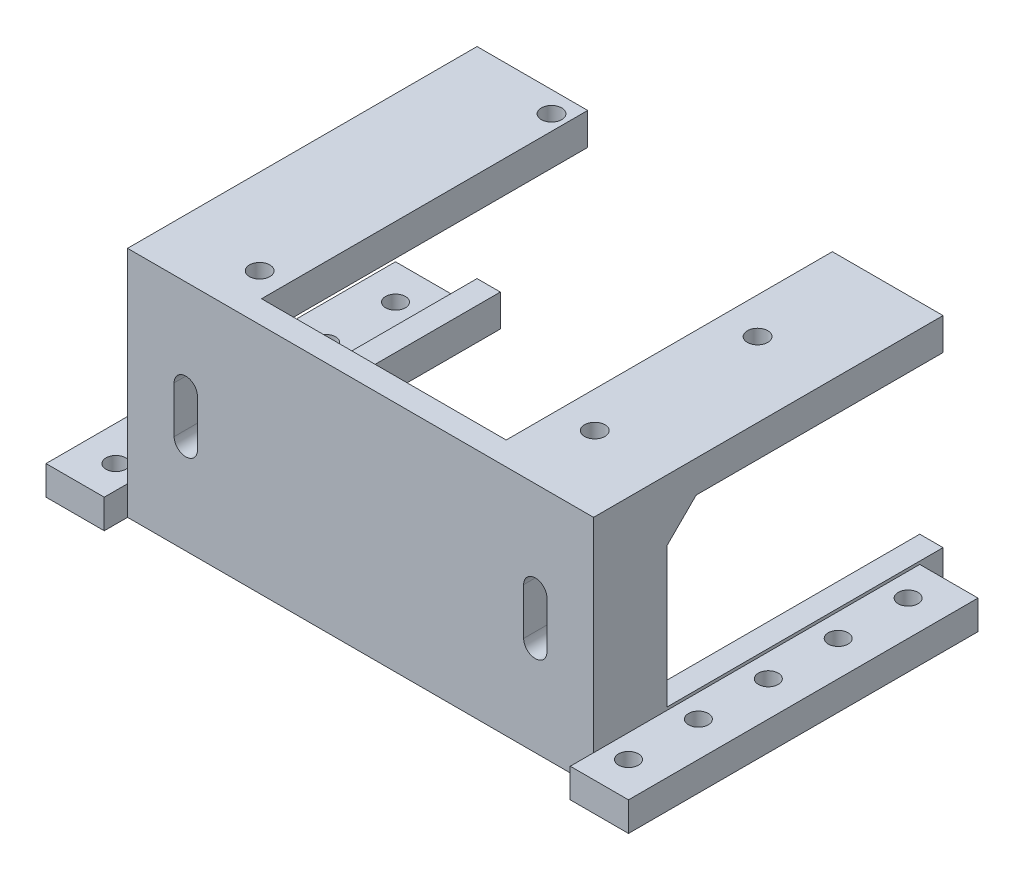
SolidWorks part; units mm, degrees
ref_plane "前视基准面" through (0, 0, 0) normal (0, 0, 1) x (1, 0, 0)
ref_plane "上视基准面" through (0, 0, 0) normal (0, 1, 0) x (1, 0, 0)
ref_plane "右视基准面" through (0, 0, 0) normal (1, 0, 0) x (0, 0, -1)
sketch "草图1" plane through (0, 0, 0) normal (0, 1, 0) x (1, 0, 0)
  line L1 (-40, -30) -> (40, -30)
  line L2 (-40, -30) -> (-40, 30)
  line L3 (-40, 30) -> (40, 30)
  line L4 (40, -30) -> (40, 30)
  line L5 (-40, -30) -> (40, 30) construction
  line L6 (-40, 30) -> (40, -30) construction
  point P0 (0, 0)
  dimension "D1" = 80
  dimension "D2" = 60
extrude "凸台-拉伸1" add sketch "草图1" along normal mid plane 40
sketch "草图2" plane through (0, 20, 0) normal (0, 1, 0) x (1, 0, 0)
  line L0 (40, 30) -> (-40, 30) construction
  line L1 (-36, -26) -> (36, -26)
  line L2 (-36, -26) -> (-36, 30)
  line L3 (-36, 30) -> (36, 30)
  line L4 (36, -26) -> (36, 30)
  line L5 (-36, -26) -> (36, 30) construction
  line L6 (-36, 30) -> (36, -26) construction
  line L7 (-40, 30) -> (-40, -30) construction
  line L8 (-40, -30) -> (40, -30) construction
  point P0 (0, 2)
  dimension "D1" = 4
  dimension "D2" = 4
extrude "切除-拉伸1" cut sketch "草图2" against normal blind 70
sketch "草图3" plane through (40, 0, 0) normal (1, 0, 0) x (0, 0, -1)
  line L0 (30, 20) -> (30, -20) construction
  line L1 (-17.3857, 14.5) -> (30, 14.5)
  line L2 (-17.3857, 14.5) -> (-17.3857, -14.5)
  line L3 (-17.3857, -14.5) -> (30, -14.5)
  line L4 (30, 14.5) -> (30, -14.5)
  line L5 (-17.3857, 14.5) -> (30, -14.5) construction
  line L6 (-17.3857, -14.5) -> (30, 14.5) construction
  point P0 (6.3072, 0)
  dimension "D1" = 29
extrude "切除-拉伸2" cut sketch "草图3" against normal blind 80
sketch "草图4" plane through (0, -20, 0) normal (0, -1, 0) x (1, 0, 0)
  line L0 (-40, -30) -> (-40, 30) construction
  line L5 (-40, 34) -> (-50, 34)
  line L6 (-40, 34) -> (-40, -26)
  line L7 (-40, -26) -> (-50, -26)
  line L8 (-50, 34) -> (-50, -26)
  line L9 (0, -22) -> (0, 22) construction
  line L10 (50, 34) -> (50, -26)
  line L11 (40, -26) -> (50, -26)
  line L12 (40, 34) -> (40, -26)
  line L13 (40, 34) -> (50, 34)
  line L14 (-40, 30) -> (40, 30) construction
  dimension "D1" = 100
  dimension "D2" = 60
  dimension "D3" = 4
extrude "凸台-拉伸2" add sketch "草图4" against normal blind 5
sketch "草图5" plane through (0, -15, 0) normal (0, 1, 0) x (1, 0, 0)
  line L0 (-50, -34) -> (-50, 26) construction
  line L1 (-50, 26) -> (-40, 26) construction
  line L2 (0, -22) -> (0, 22) construction
  circle A0 centre (-44, 20) radius 1.7
  circle A1 centre (-44, 8) radius 1.7
  circle A2 centre (-44, -4) radius 1.7
  circle A3 centre (-44, -16) radius 1.7
  circle A4 centre (-44, -28) radius 1.7
  circle A5 centre (44, -28) radius 1.7
  circle A6 centre (44, -16) radius 1.7
  circle A7 centre (44, -4) radius 1.7
  circle A8 centre (44, 8) radius 1.7
  circle A9 centre (44, 20) radius 1.7
  dimension "D1" = 3.4
  dimension "D2" = 6
  dimension "D3" = 6
  dimension "D4" = 5
extrude "切除-拉伸3" cut sketch "草图5" against normal blind 25
sketch "草图6" plane through (0, 20, 0) normal (0, 1, 0) x (1, 0, 0)
  line L0 (-36, -26) -> (36, -26) construction
  line L1 (-36, 30) -> (-21, 30)
  line L2 (-36, 30) -> (-36, -26)
  line L3 (-36, -26) -> (-21, -26)
  line L4 (-21, 30) -> (-21, -26)
  line L5 (0, -22) -> (0, 22) construction
  line L6 (21, 30) -> (21, -26)
  line L7 (36, -26) -> (21, -26)
  line L8 (36, 30) -> (36, -26)
  line L9 (36, 30) -> (21, 30)
  dimension "D1" = 15
extrude "凸台-拉伸3" add sketch "草图6" against normal up to surface (5.5 mm away) up to face at (-38, 14.5, -6.3072)
sketch "草图8" plane through (0, 20, 0) normal (0, 1, 0) x (1, 0, 0)
  circle A0 centre (-25.32, -22) radius 1.75
  circle A1 centre (-23.61, 26.395) radius 1.75
  circle A2 centre (27.2, 10.96) radius 1.75
  circle A3 centre (27.2, -17) radius 1.75
  dimension "D1" = 3.5
  dimension "D2" = 3.5
  dimension "D3" = 3.5
  dimension "D4" = 3.5
extrude "切除-拉伸5" cut sketch "草图8" against normal blind 10
chamfer "倒角1" distance 5 angle 45 1 edges at (38, 14.5, 17.3857)
sketch "草图10" plane through (0, 0, 30) normal (0, 0, 1) x (1, 0, 0)
  line L2 (-30, 4) -> (-30, -4) construction
  line L3 (-28, 4) -> (-28, -4)
  line L4 (-32, 4) -> (-32, -4)
  line L5 (0, -22) -> (0, 22) construction
  line L6 (30, 4) -> (30, -4) construction
  line L7 (28, 4) -> (28, -4)
  line L8 (32, 4) -> (32, -4)
  arc A2 (-28, 4) -> (-32, 4) centre (-30, 4) ccw
  arc A3 (-32, -4) -> (-28, -4) centre (-30, -4) ccw
  arc A4 (28, 4) -> (32, 4) centre (30, 4) cw
  arc A5 (32, -4) -> (28, -4) centre (30, -4) cw
  point P2 (-30, 0)
  point P12 (30, 0)
  dimension "D1" = 8
  dimension "D2" = 30
  dimension "D3" = 2
extrude "切除-拉伸8" cut sketch "草图10" against normal blind 10
